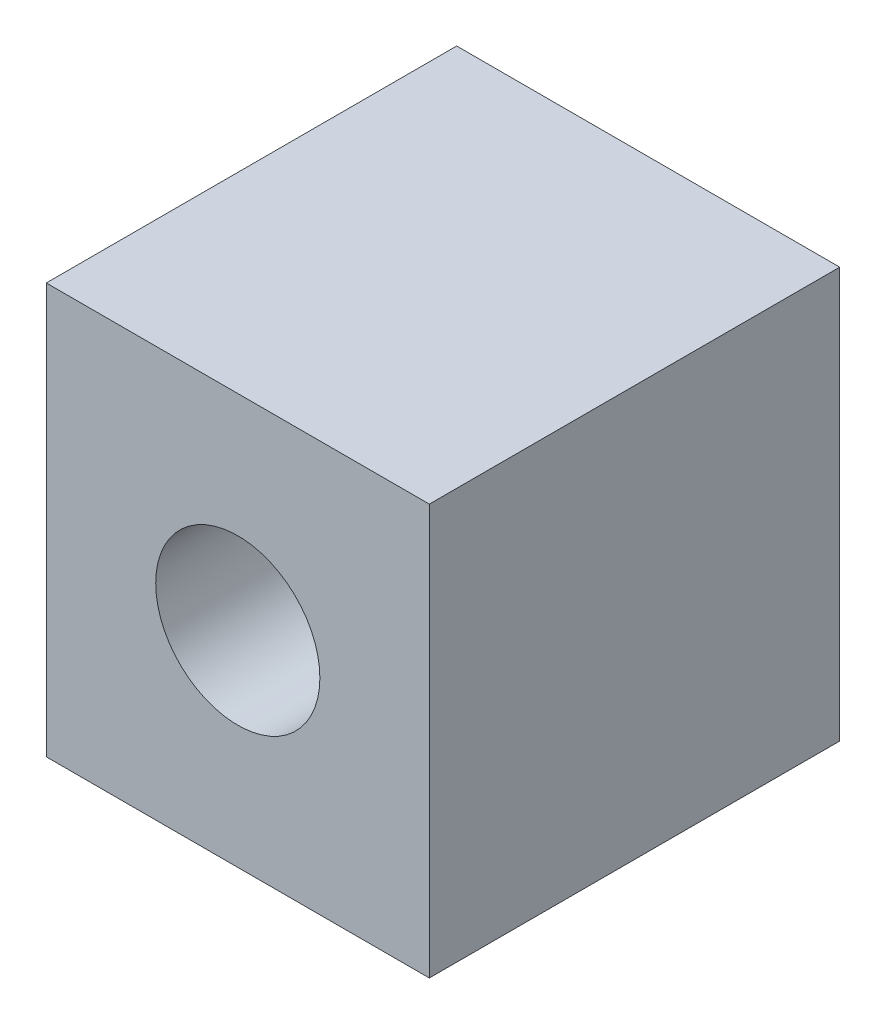
SolidWorks part; units mm, degrees
ref_plane "Front Plane" through (0, 0, 0) normal (0, 0, 1) x (1, 0, 0)
ref_plane "Top Plane" through (0, 0, 0) normal (0, 1, 0) x (1, 0, 0)
ref_plane "Right Plane" through (0, 0, 0) normal (1, 0, 0) x (0, 0, -1)
sketch "Sketch1" plane through (0, 0, 0) normal (0, 1, 0) x (1, 0, 0)
  line L1 (-14, 0) -> (-14, -15)
  line L2 (-14, -15) -> (14, -15)
  line L3 (14, -15) -> (14, 15)
  line L4 (14, 15) -> (-14, 15)
  line L5 (-14, 15) -> (-14, 0)
extrude "Boss-Extrude1" add sketch "Sketch1" along normal blind 30
sketch "Sketch2" plane through (0, 0, 15) normal (0, 0, 1) x (1, 0, 0)
  circle A1 centre (0, 15) radius 6
extrude "Cut-Extrude1" cut sketch "Sketch2" against normal through all
